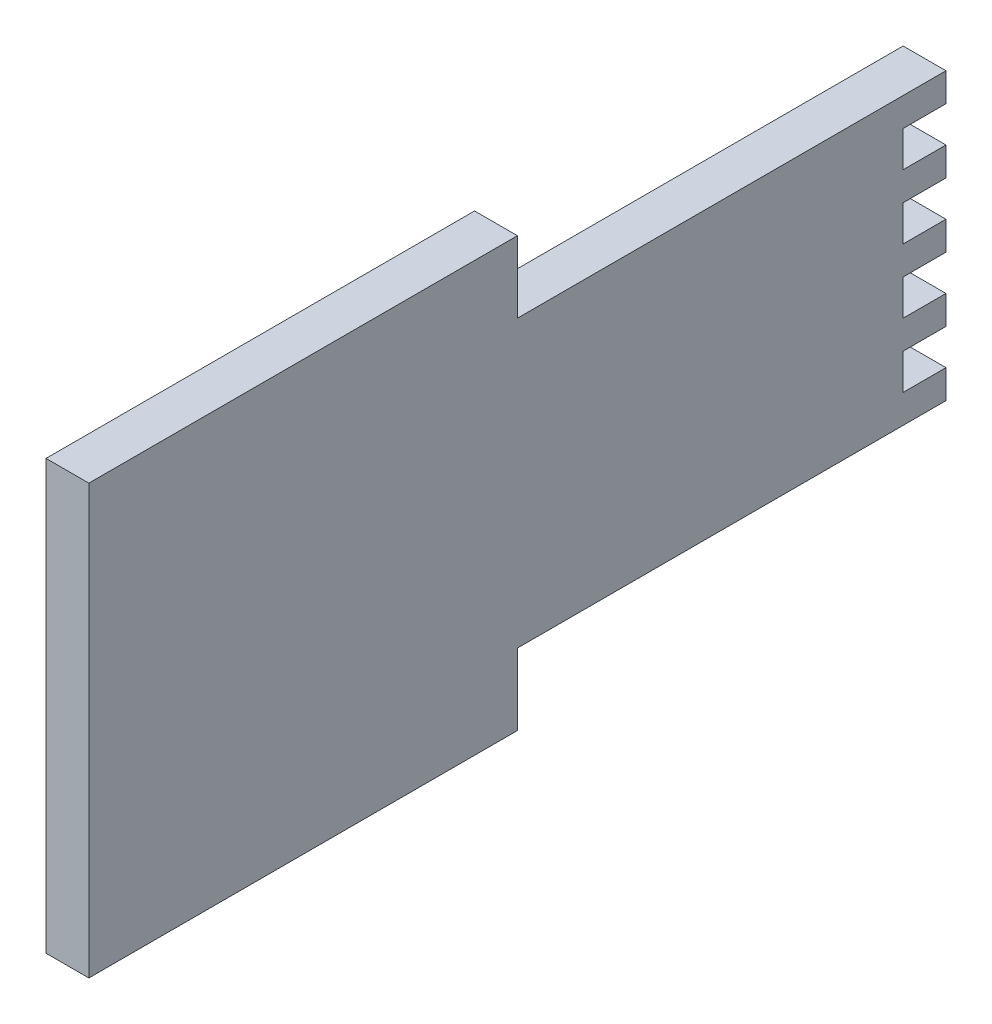
SolidWorks part; units mm, degrees
ref_plane "Front Plane" through (0, 0, 0) normal (0, 0, 1) x (1, 0, 0)
ref_plane "Top Plane" through (0, 0, 0) normal (0, 1, 0) x (1, 0, 0)
ref_plane "Right Plane" through (0, 0, 0) normal (1, 0, 0) x (0, 0, -1)
sketch "Sketch1" plane through (0, 0, 0) normal (1, 0, 0) x (0, 0, -1)
  line L0 (30, 10) -> (0, 10)
  line L1 (0, 10) -> (0, 15)
  line L2 (0, 15) -> (-30, 15)
  line L3 (-30, 15) -> (-30, -15)
  line L4 (-30, -15) -> (0, -15)
  line L5 (0, -15) -> (0, -10)
  line L6 (0, -10) -> (30, -10)
  line L7 (30, -10) -> (30, -8)
  line L8 (30, -8) -> (27, -8)
  line L9 (27, -8) -> (27, -5.5)
  line L10 (27, -5.5) -> (30, -5.5)
  line L11 (30, -5.5) -> (30, -3.5)
  line L12 (30, -3.5) -> (27, -3.5)
  line L13 (27, -3.5) -> (27, -1)
  line L14 (27, -1) -> (30, -1)
  line L15 (30, -1) -> (30, 1)
  line L16 (30, 1) -> (27, 1)
  line L17 (27, 1) -> (27, 3.5)
  line L18 (27, 3.5) -> (30, 3.5)
  line L19 (30, 3.5) -> (30, 5.5)
  line L20 (30, 5.5) -> (27, 5.5)
  line L21 (27, 5.5) -> (27, 8)
  line L22 (27, 8) -> (30, 8)
  line L23 (30, 8) -> (30, 10)
  point P9 (30, 0)
  point P25 (-30, 0)
  dimension "D1" = 2
  dimension "D2" = 2.5
  dimension "D3" = 30
  dimension "D4" = 30
  dimension "D5" = 30
  dimension "D6" = 3
extrude "Boss-Extrude1" add sketch "Sketch1" along normal blind 3
